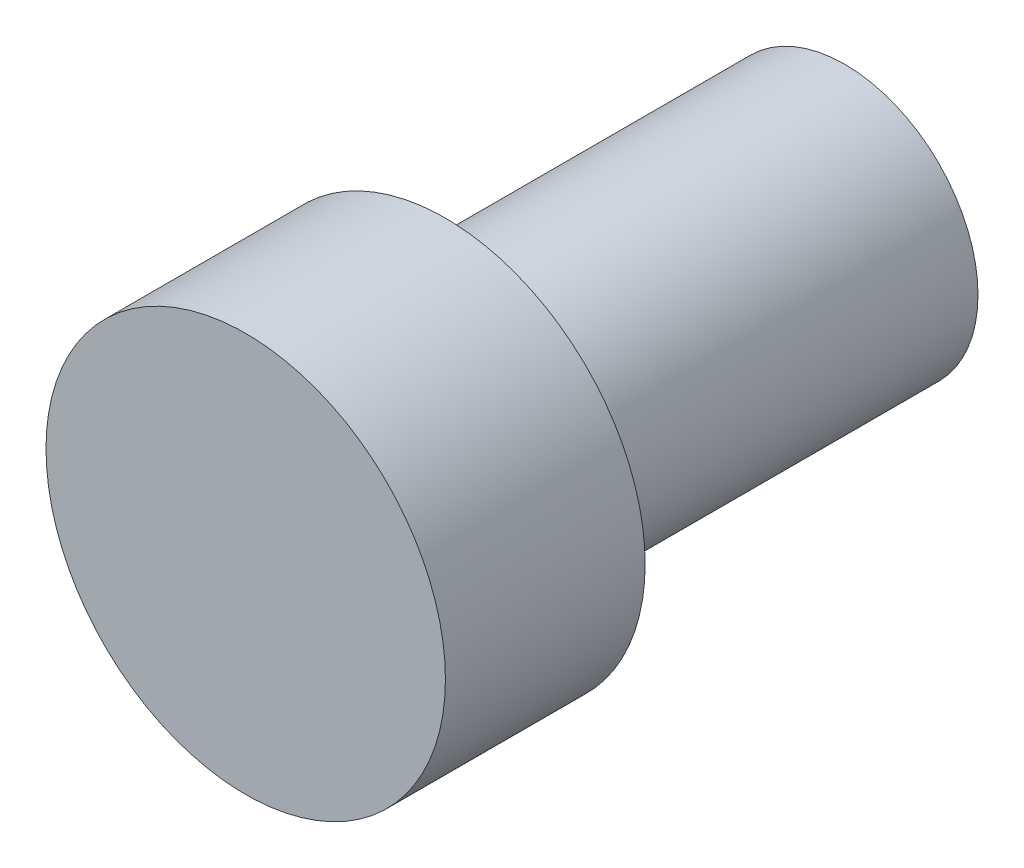
SolidWorks part; units mm, degrees
ref_plane "前视基准面" through (0, 0, 0) normal (0, 0, 1) x (1, 0, 0)
ref_plane "上视基准面" through (0, 0, 0) normal (0, 1, 0) x (1, 0, 0)
ref_plane "右视基准面" through (0, 0, 0) normal (1, 0, 0) x (0, 0, -1)
sketch "草图1" plane through (0, 0, 0) normal (0, 0, 1) x (1, 0, 0)
  circle A0 centre (0, 0) radius 2
  dimension "D1" = 4
extrude "凸台-拉伸1" add sketch "草图1" along normal blind 6
sketch "草图2" plane through (0, 0, 6) normal (0, 0, 1) x (1, 0, 0)
  circle A0 centre (0, 0) radius 3
  dimension "D1" = 6
extrude "凸台-拉伸2" add sketch "草图2" along normal blind 3
